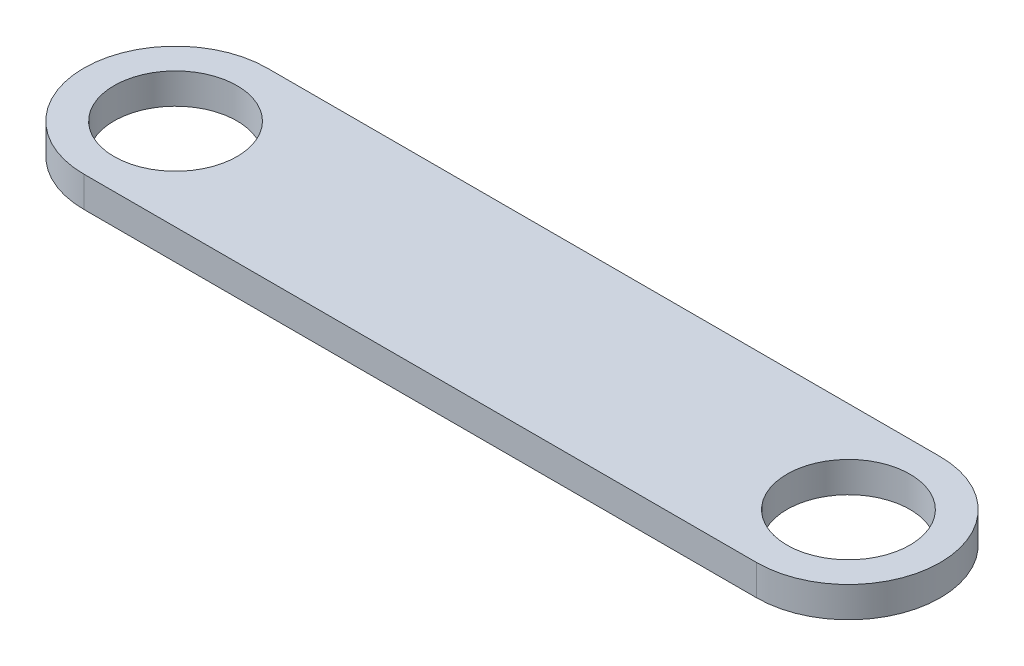
SolidWorks part; units mm, degrees
ref_plane "Front Plane" through (0, 0, 0) normal (0, 0, 1) x (1, 0, 0)
ref_plane "Top Plane" through (0, 0, 0) normal (0, 1, 0) x (1, 0, 0)
ref_plane "Right Plane" through (0, 0, 0) normal (1, 0, 0) x (0, 0, -1)
sketch "Sketch1" plane through (0, 0, 0) normal (0, 1, 0) x (1, 0, 0)
  line L0 (-27.5, 0) -> (27.5, 0) construction
  line L1 (-27.5, 7.5) -> (27.5, 7.5)
  line L2 (-27.5, -7.5) -> (27.5, -7.5)
  arc A0 (-27.5, 7.5) -> (-27.5, -7.5) centre (-27.5, 0) ccw
  arc A1 (27.5, -7.5) -> (27.5, 7.5) centre (27.5, 0) ccw
  circle A2 centre (-27.5, 0) radius 5.025
  circle A3 centre (27.5, 0) radius 5.025
  point P2 (0, 0)
  dimension "D3" = 10.05
  dimension "D1" = 27.5
  dimension "D2" = 7.5
extrude "Boss-Extrude1" add sketch "Sketch1" along normal blind 2.5
